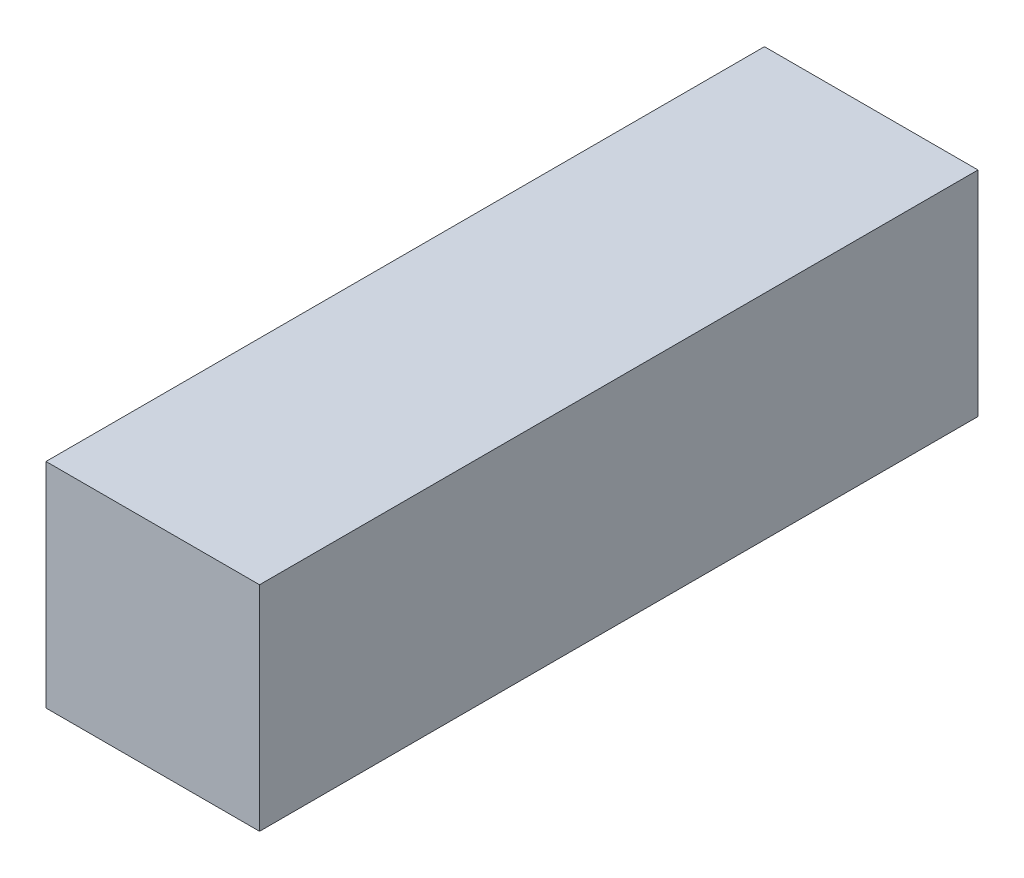
SolidWorks part; units mm, degrees
material "Pine"
ref_plane "Front Plane" through (0, 0, 0) normal (0, 0, 1) x (1, 0, 0)
ref_plane "Top Plane" through (0, 0, 0) normal (0, 1, 0) x (1, 0, 0)
ref_plane "Right Plane" through (0, 0, 0) normal (1, 0, 0) x (0, 0, -1)
sketch "Sketch1" plane through (0, 0, 0) normal (0, 1, 0) x (1, 0, 0)
  line L53 (-9.525, 0) -> (9.525, 0)
  line L54 (-9.525, 0) -> (-9.525, -64.0913)
  line L55 (-9.525, -64.0913) -> (9.525, -64.0913)
  line L56 (9.525, 0) -> (9.525, -64.0913)
  point P4 (0, 0)
  point P8 (-32.0116, 59.7088)
  point P10 (0, 0)
  dimension "D1" = 19.05
extrude "Boss-Extrude1" add sketch "Sketch1" along normal blind 19.05
